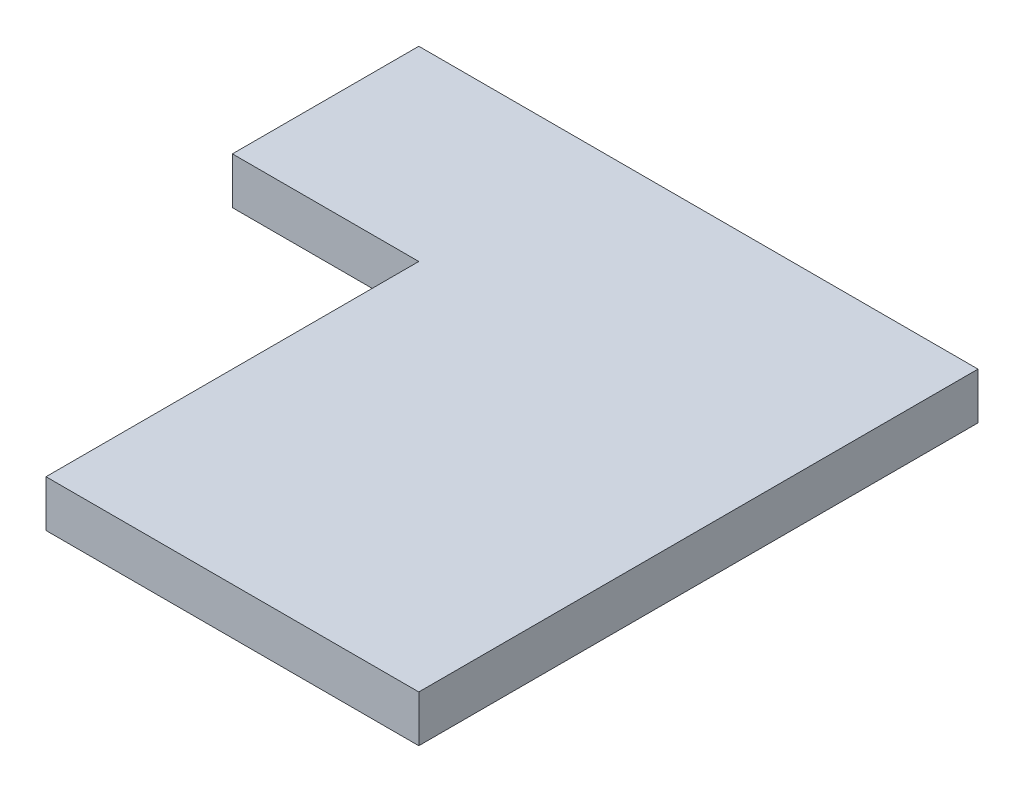
SolidWorks part; units mm, degrees
ref_plane "前视基准面" through (0, 0, 0) normal (0, 0, 1) x (1, 0, 0)
ref_plane "上视基准面" through (0, 0, 0) normal (0, 1, 0) x (1, 0, 0)
ref_plane "右视基准面" through (0, 0, 0) normal (1, 0, 0) x (0, 0, -1)
sketch "草图1" plane through (0, 0, 0) normal (0, 1, 0) x (1, 0, 0)
  line L1 (-1200, 1200) -> (1200, 1200)
  line L2 (-1200, 1200) -> (-1200, -1200)
  line L3 (-1200, -1200) -> (1200, -1200)
  line L4 (1200, 1200) -> (1200, -1200)
  line L5 (0, -1200) -> (0, 1200) construction
  line L6 (-1200, 0) -> (1200, 0) construction
  point P0 (0, 0)
  dimension "D1" = 2400
  dimension "D2" = 2400
sketch "草图2" plane through (0, 0, 0) normal (0, 1, 0) x (1, 0, 0)
  line L3 (-1200, 1200) -> (-1200, -1200) construction
  line L4 (-1200, 400) -> (-1200, -1200)
  line L5 (-1200, -1200) -> (1200, -1200) construction
  line L6 (-1200, -1200) -> (-400, -1200)
  line L7 (-1200, 400) -> (-400, 400)
  line L8 (-400, 400) -> (-400, -1200)
  dimension "D1" = 1600
  dimension "D2" = 800
extrude "凸台-拉伸1" add sketch "草图1" along normal blind 200
extrude "切除-拉伸1" cut sketch "草图2" along normal blind 200
